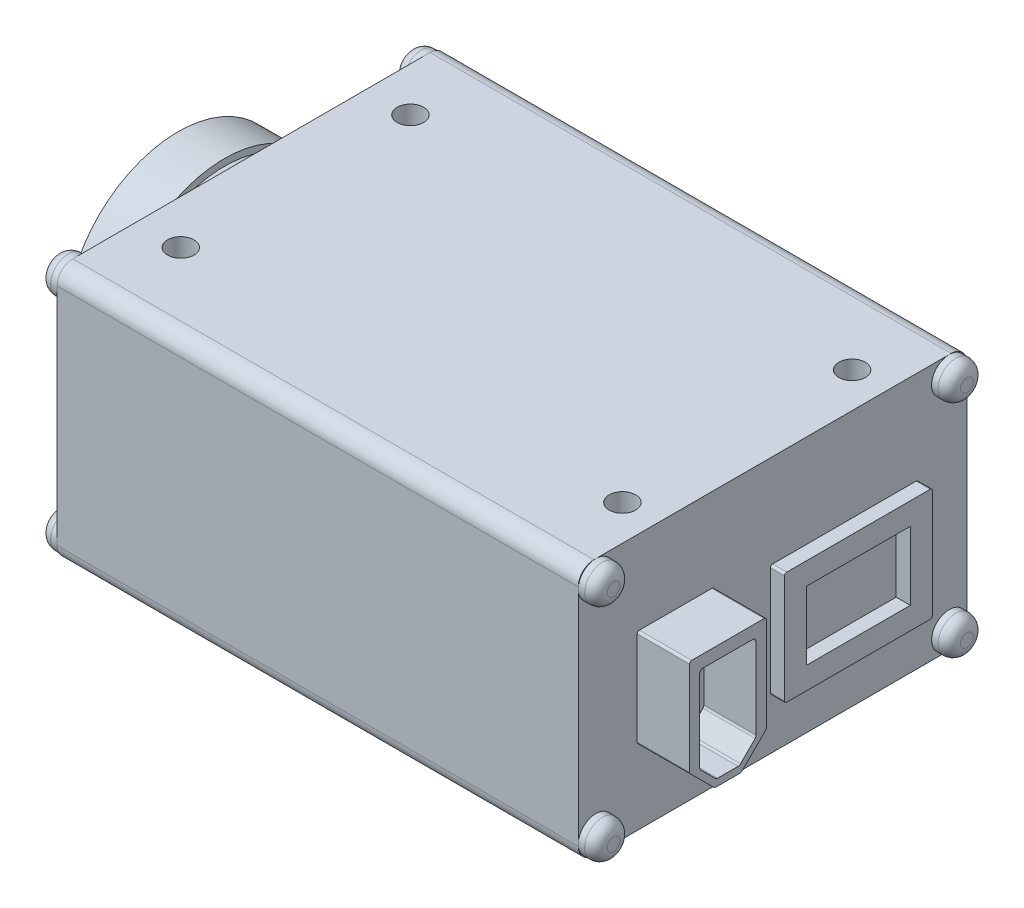
SolidWorks part; units mm, degrees
ref_plane "Front Plane" through (0, 0, 0) normal (0, 0, 1) x (1, 0, 0)
ref_plane "Top Plane" through (0, 0, 0) normal (0, 1, 0) x (1, 0, 0)
ref_plane "Right Plane" through (0, 0, 0) normal (1, 0, 0) x (0, 0, -1)
sketch "Sketch1" plane through (0, 0, 0) normal (0, 1, 0) x (1, 0, 0)
  line L0 (0, 0) -> (59, 0) construction
  line L1 (0, -22) -> (59, -22)
  line L2 (0, -22) -> (0, 22)
  line L3 (0, 22) -> (59, 22)
  line L4 (59, -22) -> (59, 22)
  dimension "D1" = 59
  dimension "D2" = 44
extrude "Extrude1" add sketch "Sketch1" along normal mid plane 29
sketch "Sketch2" plane through (0, 0, 0) normal (-1, 0, 0) x (0, 0, 1)
  circle A0 centre (0, 0) radius 12.7
  circle A1 centre (0, 0) radius 10.922
  dimension "D1" = 25.4
  dimension "D2" = 1.778
extrude "Extrude2" add sketch "Sketch2" along normal blind 8.3
sketch "Sketch3" plane through (0, 0, 0) normal (0, 1, 0) x (1, 0, 0)
  line L0 (0, 12.7) -> (-8.3, 12.7) construction
  line L1 (-3.048, 12.7) -> (0, 12.7)
  line L2 (-3.048, 12.7) -> (-3.048, 11.938)
  line L3 (-3.048, 11.938) -> (0, 11.938)
  line L4 (0, 12.7) -> (0, 11.938)
  line L5 (0, 22) -> (0, -22) construction
  line L6 (0, 0) -> (-11.8457, 0) construction
  dimension "D1" = 0.762
  dimension "D2" = 3.048
revolve "Cut-Revolve1" cut sketch "Sketch3" angle 360 about L6
sketch "Sketch4" plane through (59, 0, 0) normal (1, 0, 0) x (0, 0, -1)
  line L0 (15.9933, -8.2822) -> (0.2533, -8.2822)
  line L1 (0.2533, 3.4678) -> (15.9933, 3.4678)
  line L2 (13.9933, -6.2822) -> (2.2533, -6.2822)
  line L3 (2.2533, 1.4678) -> (13.9933, 1.4678)
  line L4 (16.2398, -8.7822) -> (-0.0002, -8.7822)
  line L5 (-0.0002, 3.9678) -> (16.2398, 3.9678)
  line L6 (15.9933, 3.4678) -> (15.9933, -8.2822)
  line L7 (13.9933, 1.4678) -> (13.9933, -6.2822)
  line L8 (-12.1295, -8.7822) -> (-9.8226, -8.7822)
  line L9 (-12.1295, -7.9974) -> (-9.8226, -7.9974)
  line L12 (16.4898, 3.7178) -> (16.4898, -8.5322)
  line L22 (-8.1761, 3.6178) -> (-13.7761, 3.6178)
  line L30 (-7.7761, -5.9508) -> (-7.7761, 3.2178)
  line L36 (-14.1761, 3.2178) -> (-14.1761, -5.9508)
  line L52 (-9.5398, -7.8803) -> (-7.8932, -6.2337)
  line L54 (-14.0589, -6.2337) -> (-12.4123, -7.8803)
  line L55 (0.2533, -8.2822) -> (0.2533, 3.4678)
  line L56 (2.2533, -6.2822) -> (2.2533, 1.4678)
  line L83 (-15.3295, -5.8286) -> (-15.3295, 4.7678)
  line L84 (-6.6295, 4.7678) -> (-6.6295, -5.8286)
  line L85 (-15.0795, 5.0178) -> (-6.8795, 5.0178)
  line L86 (-12.5527, -8.709) -> (-15.2563, -6.0054)
  line L87 (-12.1295, -8.7822) -> (-12.376, -8.7822)
  line L89 (-9.5831, -8.7822) -> (-9.8226, -8.7822)
  line L90 (-6.7027, -6.0054) -> (-9.4063, -8.709)
  line L91 (-0.2502, -8.5322) -> (-0.2502, 3.7178)
  arc A3 (16.2398, -8.7822) -> (16.4898, -8.5322) centre (16.2398, -8.5322) ccw
  arc A4 (16.4898, 3.7178) -> (16.2398, 3.9678) centre (16.2398, 3.7178) ccw
  arc A5 (16.4898, 3.7178) -> (16.2398, 3.9678) centre (16.2398, 3.7178) ccw
  arc A6 (-7.7761, 3.2178) -> (-8.1761, 3.6178) centre (-8.1761, 3.2178) ccw
  arc A9 (-13.7761, 3.6178) -> (-14.1761, 3.2178) centre (-13.7761, 3.2178) ccw
  arc A10 (-14.1761, -5.9508) -> (-14.0589, -6.2337) centre (-13.7761, -5.9508) ccw
  arc A12 (-12.4123, -7.8803) -> (-12.1295, -7.9974) centre (-12.1295, -7.5974) ccw
  arc A14 (-7.8932, -6.2337) -> (-7.7761, -5.9508) centre (-8.1761, -5.9508) ccw
  arc A16 (-9.8226, -7.9974) -> (-9.5398, -7.8803) centre (-9.8226, -7.5974) ccw
  arc A24 (-14.6149, -6.6468) -> (-14.5761, -6.6177) centre (-15.7952, -5.0322) ccw
  arc A26 (-15.0795, 5.0178) -> (-15.3295, 4.7678) centre (-15.0795, 4.7678) ccw
  arc A27 (-6.7027, -6.0054) -> (-6.6295, -5.8286) centre (-6.8795, -5.8286) ccw
  arc A28 (-6.6295, 4.7678) -> (-6.8795, 5.0178) centre (-6.8795, 4.7678) ccw
  arc A29 (-15.3295, -5.8286) -> (-15.2563, -6.0054) centre (-15.0795, -5.8286) ccw
  arc A30 (-12.5527, -8.709) -> (-12.376, -8.7822) centre (-12.376, -8.5322) ccw
  arc A31 (-9.5831, -8.7822) -> (-9.4063, -8.709) centre (-9.5831, -8.5322) ccw
  arc A32 (-0.0002, 3.9678) -> (-0.2502, 3.7178) centre (-0.0002, 3.7178) ccw
  arc A33 (-0.2502, -8.5322) -> (-0.0002, -8.7822) centre (-0.0002, -8.5322) ccw
  point P0 (16.4898, -2.4072)
fillet "Fillet3" radius 1.778 4 edges at (29.5, -14.5, 22) (29.5, -14.5, -22) (29.5, 14.5, 22) (29.5, 14.5, -22)
sketch "Sketch5" plane through (59, 0, 0) normal (1, 0, 0) x (0, 0, -1)
  line L0 (0, 0) -> (0, 17.0195) construction
  line L1 (0, 0) -> (-28.9559, 0) construction
  line L2 (-22, 12.722) -> (-22, -12.722) construction
  line L3 (-20.222, 14.5) -> (20.222, 14.5) construction
  circle A0 centre (-20, 12.5) radius 2
  circle A1 centre (20, 12.5) radius 2
  circle A2 centre (20, -12.5) radius 2
  circle A3 centre (-20, -12.5) radius 2
  dimension "D1" = 4
extrude "Extrude3" add sketch "Sketch5" along normal blind 2 and the other way offset from surface (61 mm away) 2 other way up to face at (0, 0, 0)
fillet "Fillet1" radius 1.27 8 edges at (-2, 12.5, -22) (61, -12.5, -22) (-2, -12.5, -22) (61, 12.5, -18) (61, 12.5, 18) (61, -12.5, 22) (-2, -12.5, 18) (-2, 12.5, 18)
sketch "Sketch6" plane through (59, 0, 0) normal (1, 0, 0) x (0, 0, -1)
  line L0 (-12.5527, -8.709) -> (-15.2563, -6.0054) construction
  line L1 (-12.1295, -8.7822) -> (-12.376, -8.7822) construction
  line L2 (-12.1295, -8.7822) -> (-9.8226, -8.7822) construction
  line L3 (-9.5831, -8.7822) -> (-9.8226, -8.7822) construction
  line L4 (-6.7027, -6.0054) -> (-9.4063, -8.709) construction
  line L5 (-6.6295, 4.7678) -> (-6.6295, -5.8286) construction
  line L6 (-15.0795, 5.0178) -> (-6.8795, 5.0178) construction
  line L7 (-15.3295, -5.8286) -> (-15.3295, 4.7678) construction
  line L8 (-12.5527, -8.709) -> (-15.2563, -6.0054)
  line L9 (-12.1295, -8.7822) -> (-12.376, -8.7822)
  line L10 (-12.1295, -8.7822) -> (-9.8226, -8.7822)
  line L11 (-9.5831, -8.7822) -> (-9.8226, -8.7822)
  line L12 (-6.7027, -6.0054) -> (-9.4063, -8.709)
  line L13 (-6.6295, 4.7678) -> (-6.6295, -5.8286)
  line L14 (-15.0795, 5.0178) -> (-6.8795, 5.0178)
  line L15 (-15.3295, -5.8286) -> (-15.3295, 4.7678)
  line L16 (-14.0589, -6.2337) -> (-12.4123, -7.8803) construction
  line L17 (-14.1761, 3.2178) -> (-14.1761, -5.9508) construction
  line L18 (-8.1761, 3.6178) -> (-13.7761, 3.6178) construction
  line L19 (-7.7761, -5.9508) -> (-7.7761, 3.2178) construction
  line L20 (-9.5398, -7.8803) -> (-7.8932, -6.2337) construction
  line L21 (-12.1295, -7.9974) -> (-9.8226, -7.9974) construction
  line L22 (-14.0589, -6.2337) -> (-12.4123, -7.8803)
  line L23 (-14.1761, 3.2178) -> (-14.1761, -5.9508)
  line L24 (-8.1761, 3.6178) -> (-13.7761, 3.6178)
  line L25 (-7.7761, -5.9508) -> (-7.7761, 3.2178)
  line L26 (-9.5398, -7.8803) -> (-7.8932, -6.2337)
  line L27 (-12.1295, -7.9974) -> (-9.8226, -7.9974)
  arc A0 (-15.3295, -5.8286) -> (-15.2563, -6.0054) centre (-15.0795, -5.8286) ccw construction
  arc A1 (-12.5527, -8.709) -> (-12.376, -8.7822) centre (-12.376, -8.5322) ccw construction
  arc A2 (-9.5831, -8.7822) -> (-9.4063, -8.709) centre (-9.5831, -8.5322) ccw construction
  arc A3 (-6.7027, -6.0054) -> (-6.6295, -5.8286) centre (-6.8795, -5.8286) ccw construction
  arc A4 (-6.6295, 4.7678) -> (-6.8795, 5.0178) centre (-6.8795, 4.7678) ccw construction
  arc A5 (-15.0795, 5.0178) -> (-15.3295, 4.7678) centre (-15.0795, 4.7678) ccw construction
  arc A6 (-15.3295, -5.8286) -> (-15.2563, -6.0054) centre (-15.0795, -5.8286) ccw
  arc A7 (-12.5527, -8.709) -> (-12.376, -8.7822) centre (-12.376, -8.5322) ccw
  arc A8 (-9.5831, -8.7822) -> (-9.4063, -8.709) centre (-9.5831, -8.5322) ccw
  arc A9 (-6.7027, -6.0054) -> (-6.6295, -5.8286) centre (-6.8795, -5.8286) ccw
  arc A10 (-6.6295, 4.7678) -> (-6.8795, 5.0178) centre (-6.8795, 4.7678) ccw
  arc A11 (-15.0795, 5.0178) -> (-15.3295, 4.7678) centre (-15.0795, 4.7678) ccw
  arc A12 (-12.4123, -7.8803) -> (-12.1295, -7.9974) centre (-12.1295, -7.5974) ccw construction
  arc A13 (-14.1761, -5.9508) -> (-14.0589, -6.2337) centre (-13.7761, -5.9508) ccw construction
  arc A14 (-13.7761, 3.6178) -> (-14.1761, 3.2178) centre (-13.7761, 3.2178) ccw construction
  arc A15 (-7.7761, 3.2178) -> (-8.1761, 3.6178) centre (-8.1761, 3.2178) ccw construction
  arc A16 (-7.8932, -6.2337) -> (-7.7761, -5.9508) centre (-8.1761, -5.9508) ccw construction
  arc A17 (-9.8226, -7.9974) -> (-9.5398, -7.8803) centre (-9.8226, -7.5974) ccw construction
  arc A18 (-12.4123, -7.8803) -> (-12.1295, -7.9974) centre (-12.1295, -7.5974) ccw
  arc A19 (-14.1761, -5.9508) -> (-14.0589, -6.2337) centre (-13.7761, -5.9508) ccw
  arc A20 (-13.7761, 3.6178) -> (-14.1761, 3.2178) centre (-13.7761, 3.2178) ccw
  arc A21 (-7.7761, 3.2178) -> (-8.1761, 3.6178) centre (-8.1761, 3.2178) ccw
  arc A22 (-7.8932, -6.2337) -> (-7.7761, -5.9508) centre (-8.1761, -5.9508) ccw
  arc A23 (-9.8226, -7.9974) -> (-9.5398, -7.8803) centre (-9.8226, -7.5974) ccw
extrude "Extrude4" add sketch "Sketch6" along normal blind 5.92
sketch "Sketch7" plane through (59, 0, 0) normal (1, 0, 0) x (0, 0, -1)
  line L0 (-0.0002, 3.9678) -> (16.2398, 3.9678) construction
  line L1 (-0.2502, -8.5322) -> (-0.2502, 3.7178) construction
  line L2 (16.2398, -8.7822) -> (-0.0002, -8.7822) construction
  line L3 (16.4898, 3.7178) -> (16.4898, -8.5322) construction
  line L4 (-0.0002, 3.9678) -> (16.2398, 3.9678)
  line L5 (-0.2502, -8.5322) -> (-0.2502, 3.7178)
  line L6 (16.2398, -8.7822) -> (-0.0002, -8.7822)
  line L7 (16.4898, 3.7178) -> (16.4898, -8.5322)
  line L8 (2.2533, -6.2822) -> (2.2533, 1.4678) construction
  line L9 (13.9933, -6.2822) -> (2.2533, -6.2822) construction
  line L10 (13.9933, 1.4678) -> (13.9933, -6.2822) construction
  line L11 (2.2533, 1.4678) -> (13.9933, 1.4678) construction
  line L12 (2.2533, -6.2822) -> (2.2533, 1.4678)
  line L13 (13.9933, -6.2822) -> (2.2533, -6.2822)
  line L14 (13.9933, 1.4678) -> (13.9933, -6.2822)
  line L15 (2.2533, 1.4678) -> (13.9933, 1.4678)
  arc A0 (-0.0002, 3.9678) -> (-0.2502, 3.7178) centre (-0.0002, 3.7178) ccw construction
  arc A1 (-0.2502, -8.5322) -> (-0.0002, -8.7822) centre (-0.0002, -8.5322) ccw construction
  arc A2 (16.2398, -8.7822) -> (16.4898, -8.5322) centre (16.2398, -8.5322) ccw construction
  arc A3 (-0.0002, 3.9678) -> (-0.2502, 3.7178) centre (-0.0002, 3.7178) ccw
  arc A4 (-0.2502, -8.5322) -> (-0.0002, -8.7822) centre (-0.0002, -8.5322) ccw
  arc A5 (16.2398, -8.7822) -> (16.4898, -8.5322) centre (16.2398, -8.5322) ccw
  arc A6 (16.4898, 3.7178) -> (16.2398, 3.9678) centre (16.2398, 3.7178) ccw construction
  arc A7 (16.4898, 3.7178) -> (16.2398, 3.9678) centre (16.2398, 3.7178) ccw
extrude "Extrude5" add sketch "Sketch7" along normal blind 1.6
hole_wizard "M3x0.5 Tapped Hole1" positions "Sketch9" profile "Sketch8" tap size "M3x0.5" standard "Ansi Metric"
sketch "Sketch9" plane through (0, 14.5, 0) normal (0, 1, 0) x (-1, 0, 0)
  line L0 (8.3, -12.7) -> (8.3, 12.7) construction
  line L1 (0, 0) -> (-59, 0) construction
  line L2 (0, -20) -> (0, 20) construction
  line L3 (-59, 20) -> (-59, -20) construction
  line L5 (-55, -13) -> (-55, 13) construction
  line L7 (-55, 0) -> (-43.1883, 0) construction
  point P0 (-55, 13)
  point P1 (-55, -13)
  point P3 (-5, -13)
  point P5 (-5, 13)
  dimension "D1" = 26
  dimension "D2" = 50
  dimension "D3" = 13.3
sketch "Sketch8" plane through (55, 14.5, 13) normal (1, 0, 0) x (0, 0, 1)
  line L0 (0, 0) -> (0, 9.2347)
  line L1 (0, 9.2347) -> (1.25, 8.4836)
  line L2 (1.25, 8.4836) -> (1.25, 5.9944)
  line L3 (1.25, 5.9944) -> (1.5, 5.9944)
  line L4 (1.5, 5.9944) -> (1.5, 0)
  line L5 (1.5, 0) -> (0, 0)
  line L10 (0, 9.2347) -> (-1.25, 8.4836) construction
  line L11 (0, -6.35) -> (0, 107.95) construction
  dimension "Tap Drill Dia." = 2.5
  dimension "Tap Drill Depth" = 8.4836
  dimension "Thread Major Dia." = 3
  dimension "Thread Depth" = 5.9944
  dimension "Drill Angle" = 118
ref_point "Point1"
ref_point "Point2"
ref_plane "Plane1" through (0, 0, 13) normal (0, 0, -1) x (-1, 0, 0)
ref_plane "Plane2" through (55, 0, 0) normal (1, 0, 0) x (0, 0, -1)
